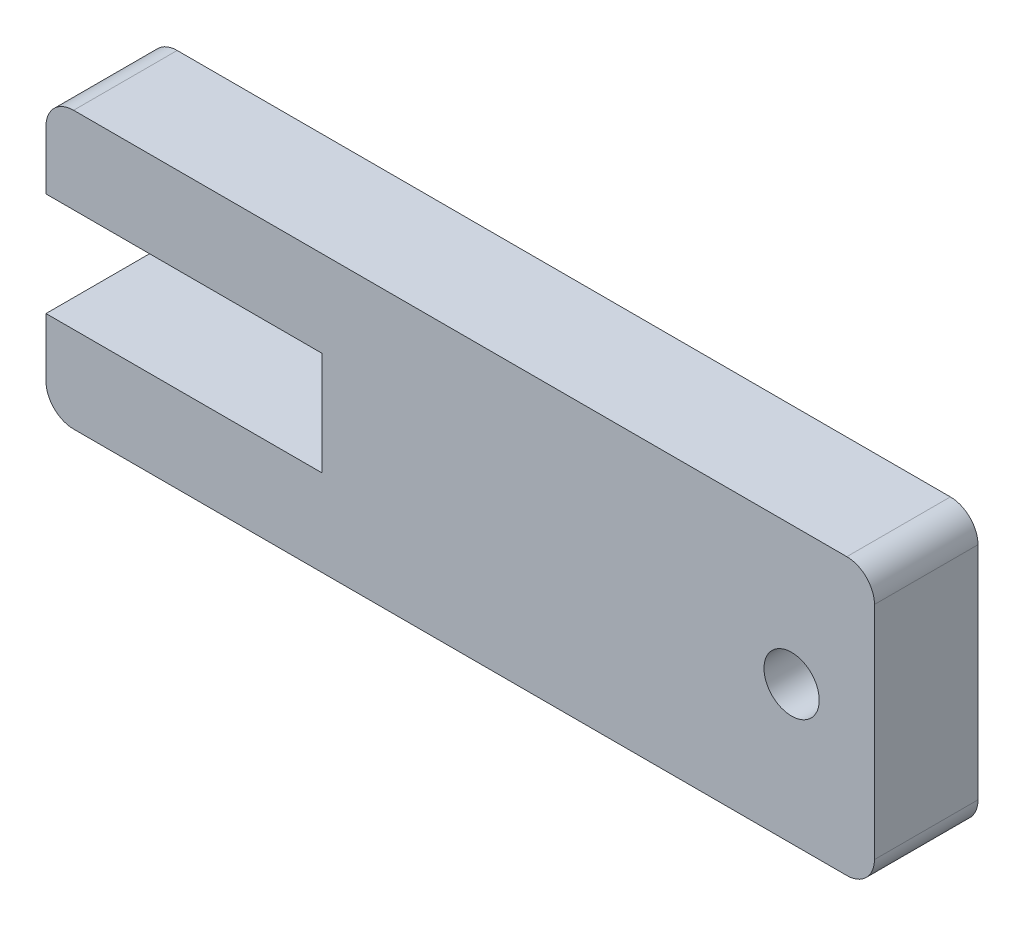
SolidWorks part; units mm, degrees
ref_plane "Front Plane" through (0, 0, 0) normal (0, 0, 1) x (1, 0, 0)
ref_plane "Top Plane" through (0, 0, 0) normal (0, 1, 0) x (1, 0, 0)
ref_plane "Right Plane" through (0, 0, 0) normal (1, 0, 0) x (0, 0, -1)
sketch "Sketch1" plane through (0, 0, 0) normal (0, 0, 1) x (1, 0, 0)
  line L0 (-12.7, 2.3813) -> (-12.7, 6.35)
  line L1 (-12.7, -2.3813) -> (0, -2.3813)
  line L3 (-12.7, 2.3813) -> (0, 2.3813)
  line L4 (0, -2.3813) -> (0, 2.3813)
  line L5 (-12.7, 6.35) -> (25.4, 6.35)
  line L6 (0, 0) -> (25.4, 0) construction
  line L7 (25.4, 6.35) -> (25.4, -6.35)
  line L8 (-12.7, -6.35) -> (25.4, -6.35)
  line L9 (-12.7, -2.3813) -> (-12.7, -6.35)
  dimension "D1" = 12.7
  dimension "D2" = 4.7625
  dimension "D3" = 25.4
  dimension "D4" = 12.7
extrude "Boss-Extrude1" add sketch "Sketch1" along normal mid plane 4.7625
fillet "Fillet1" radius 1.27 4 edges at (-12.7, -6.35, 0) (25.4, -6.35, 0) (25.4, 6.35, 0) (-12.7, 6.35, 0)
sketch "Sketch2" plane through (0, 0, 2.3813) normal (0, 0, 1) x (1, 0, 0)
  line L0 (0, 0) -> (25.4, 0) construction
  line L1 (25.4, -5.08) -> (25.4, 5.08) construction
  circle A0 centre (21.59, 0) radius 1.27
  dimension "D1" = 2.54
  dimension "D2" = 2.54
extrude "Cut-Extrude1" cut sketch "Sketch2" against normal through all
equation "\"D2@Sketch1\"=\"thick@FullAssem.Assembly\""
equation "\"D1@Sketch2\"=\"rodThick@FullAssem.Assembly\""
equation "\"D1@Boss-Extrude1\"=\"thick@FullAssem.Assembly\""
